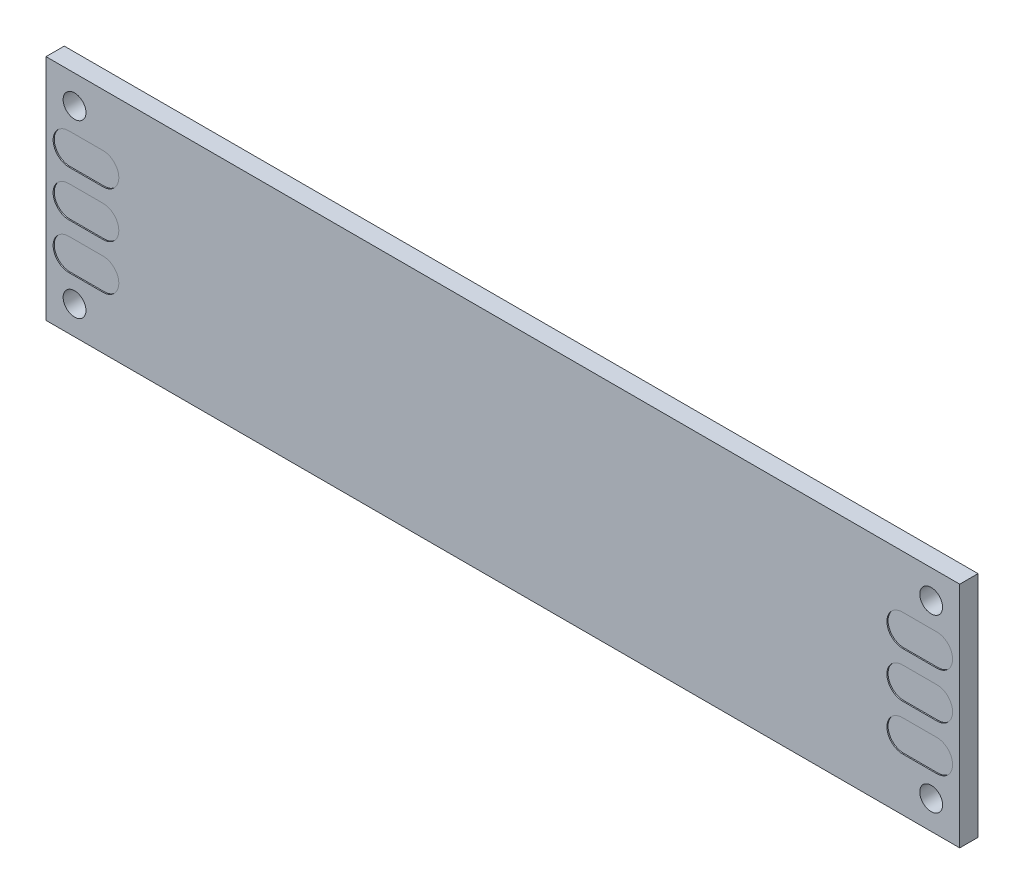
SolidWorks part; units mm, degrees
ref_plane "Спереди" through (0, 0, 0) normal (0, 0, 1) x (1, 0, 0)
ref_plane "Сверху" through (0, 0, 0) normal (0, 1, 0) x (1, 0, 0)
ref_plane "Справа" through (0, 0, 0) normal (1, 0, 0) x (0, 0, -1)
sketch "Эскиз1" plane through (0, 0, 0) normal (0, 0, 1) x (1, 0, 0)
  line L1 (-40, 10) -> (40, 10)
  line L2 (-40, 10) -> (-40, -10)
  line L3 (-40, -10) -> (40, -10)
  line L4 (40, 10) -> (40, -10)
  line L5 (-40, 10) -> (40, -10) construction
  line L6 (-40, -10) -> (40, 10) construction
  line L7 (-37.5, 7.5) -> (37.5, 7.5) construction
  line L8 (-37.5, 7.5) -> (-37.5, -7.5) construction
  line L9 (-37.5, -7.5) -> (37.5, -7.5) construction
  line L10 (37.5, 7.5) -> (37.5, -7.5) construction
  line L11 (-37.5, 7.5) -> (37.5, -7.5) construction
  line L12 (-37.5, -7.5) -> (37.5, 7.5) construction
  circle A0 centre (-37.5, 7.5) radius 1
  circle A1 centre (-37.5, -7.5) radius 1
  circle A2 centre (37.5, -7.5) radius 1
  circle A3 centre (37.5, 7.5) radius 1
  point P0 (0, 0)
  point P6 (0, 0)
  dimension "D5" = 2
  dimension "D1" = 20
  dimension "D2" = 80
  dimension "D3" = 15
  dimension "D4" = 75
extrude "Бобышка-Вытянуть1" add sketch "Эскиз1" along normal blind 1.6
sketch "Эскиз2" plane through (0, 0, 1.6) normal (0, 0, 1) x (1, 0, 0)
  line L0 (-38, -4) -> (-35, -4) construction
  line L1 (-38, -2.625) -> (-35, -2.625)
  line L2 (-38, -5.375) -> (-35, -5.375)
  line L3 (-38, 0) -> (-35, 0) construction
  line L4 (-38, 1.375) -> (-35, 1.375)
  line L5 (-38, -1.375) -> (-35, -1.375)
  line L6 (-38, 4) -> (-35, 4) construction
  line L7 (-38, 5.375) -> (-35, 5.375)
  line L8 (-38, 2.625) -> (-35, 2.625)
  line L9 (-40, 0) -> (40, 0) construction
  line L10 (-40, 10) -> (-40, -10) construction
  line L11 (40, -10) -> (40, 10) construction
  line L12 (0, 10) -> (0, -10) construction
  line L13 (40, 10) -> (-40, 10) construction
  line L14 (-40, -10) -> (40, -10) construction
  line L15 (38, -4) -> (35, -4) construction
  line L16 (38, -2.625) -> (35, -2.625)
  line L17 (38, -5.375) -> (35, -5.375)
  line L18 (38, 0) -> (35, 0) construction
  line L19 (38, 1.375) -> (35, 1.375)
  line L20 (38, -1.375) -> (35, -1.375)
  line L21 (38, 4) -> (35, 4) construction
  line L22 (38, 5.375) -> (35, 5.375)
  line L23 (38, 2.625) -> (35, 2.625)
  arc A0 (-38, -2.625) -> (-38, -5.375) centre (-38, -4) ccw
  arc A1 (-35, -5.375) -> (-35, -2.625) centre (-35, -4) ccw
  arc A2 (-38, 1.375) -> (-38, -1.375) centre (-38, 0) ccw
  arc A3 (-35, -1.375) -> (-35, 1.375) centre (-35, 0) ccw
  arc A4 (-38, 5.375) -> (-38, 2.625) centre (-38, 4) ccw
  arc A5 (-35, 2.625) -> (-35, 5.375) centre (-35, 4) ccw
  arc A6 (38, -2.625) -> (38, -5.375) centre (38, -4) cw
  arc A7 (35, -5.375) -> (35, -2.625) centre (35, -4) cw
  arc A8 (38, 1.375) -> (38, -1.375) centre (38, 0) cw
  arc A9 (35, -1.375) -> (35, 1.375) centre (35, 0) cw
  arc A10 (38, 5.375) -> (38, 2.625) centre (38, 4) cw
  arc A11 (35, 2.625) -> (35, 5.375) centre (35, 4) cw
  point P2 (-36.5, -4)
  point P9 (-36.5, 0)
  point P17 (-36.5, 4)
  point P27 (0, 0)
  point P36 (36.5, -4)
  point P43 (36.5, 0)
  point P50 (36.5, 4)
  dimension "D2" = 4
  dimension "D3" = 3
  dimension "D4" = 2.75
  dimension "D5" = 3.5
  dimension "D1" = 3
extrude "Вырез-Вытянуть1" cut sketch "Эскиз2" against normal blind 0.1
sketch "Эскиз3" plane through (0, 0, 0) normal (0, 0, -1) x (-1, 0, 0)
  line L2 (38, 1.375) -> (35, 1.375)
  line L3 (35, -1.375) -> (38, -1.375)
  line L4 (38, 1.375) -> (35, 1.375)
  line L5 (35, -1.375) -> (38, -1.375)
  line L6 (38, -2.625) -> (35, -2.625)
  line L7 (35, -5.375) -> (38, -5.375)
  line L8 (38, -2.625) -> (35, -2.625)
  line L9 (35, -5.375) -> (38, -5.375)
  line L10 (38, 5.375) -> (35, 5.375)
  line L11 (35, 2.625) -> (38, 2.625)
  line L12 (38, 5.375) -> (35, 5.375)
  line L13 (35, 2.625) -> (38, 2.625)
  line L14 (-35, 1.375) -> (-38, 1.375)
  line L15 (-38, -1.375) -> (-35, -1.375)
  line L16 (-35, 1.375) -> (-38, 1.375)
  line L17 (-38, -1.375) -> (-35, -1.375)
  line L18 (-35, -2.625) -> (-38, -2.625)
  line L19 (-38, -5.375) -> (-35, -5.375)
  line L20 (-35, -2.625) -> (-38, -2.625)
  line L21 (-38, -5.375) -> (-35, -5.375)
  line L22 (-35, 5.375) -> (-38, 5.375)
  line L23 (-38, 2.625) -> (-35, 2.625)
  line L24 (-35, 5.375) -> (-38, 5.375)
  line L25 (-38, 2.625) -> (-35, 2.625)
  arc A2 (35, 1.375) -> (35, -1.375) centre (35, 0) ccw
  arc A3 (38, -1.375) -> (38, 1.375) centre (38, 0) ccw
  arc A4 (35, 1.375) -> (35, -1.375) centre (35, 0) ccw
  arc A5 (38, -1.375) -> (38, 1.375) centre (38, 0) ccw
  arc A6 (35, -2.625) -> (35, -5.375) centre (35, -4) ccw
  arc A7 (38, -5.375) -> (38, -2.625) centre (38, -4) ccw
  arc A8 (35, -2.625) -> (35, -5.375) centre (35, -4) ccw
  arc A9 (38, -5.375) -> (38, -2.625) centre (38, -4) ccw
  arc A10 (35, 5.375) -> (35, 2.625) centre (35, 4) ccw
  arc A11 (38, 2.625) -> (38, 5.375) centre (38, 4) ccw
  arc A12 (35, 5.375) -> (35, 2.625) centre (35, 4) ccw
  arc A13 (38, 2.625) -> (38, 5.375) centre (38, 4) ccw
  arc A14 (-35, -1.375) -> (-35, 1.375) centre (-35, 0) ccw
  arc A15 (-38, 1.375) -> (-38, -1.375) centre (-38, 0) ccw
  arc A16 (-35, -1.375) -> (-35, 1.375) centre (-35, 0) ccw
  arc A17 (-38, 1.375) -> (-38, -1.375) centre (-38, 0) ccw
  arc A18 (-35, -5.375) -> (-35, -2.625) centre (-35, -4) ccw
  arc A19 (-38, -2.625) -> (-38, -5.375) centre (-38, -4) ccw
  arc A20 (-35, -5.375) -> (-35, -2.625) centre (-35, -4) ccw
  arc A21 (-38, -2.625) -> (-38, -5.375) centre (-38, -4) ccw
  arc A22 (-35, 2.625) -> (-35, 5.375) centre (-35, 4) ccw
  arc A23 (-38, 5.375) -> (-38, 2.625) centre (-38, 4) ccw
  arc A24 (-35, 2.625) -> (-35, 5.375) centre (-35, 4) ccw
  arc A25 (-38, 5.375) -> (-38, 2.625) centre (-38, 4) ccw
  dimension "D1" = 0
  dimension "D2" = 0
  dimension "D3" = 0
  dimension "D4" = 0
  dimension "D5" = 0
  dimension "D6" = 0
extrude "Вырез-Вытянуть2" cut sketch "Эскиз3" against normal blind 0.1
